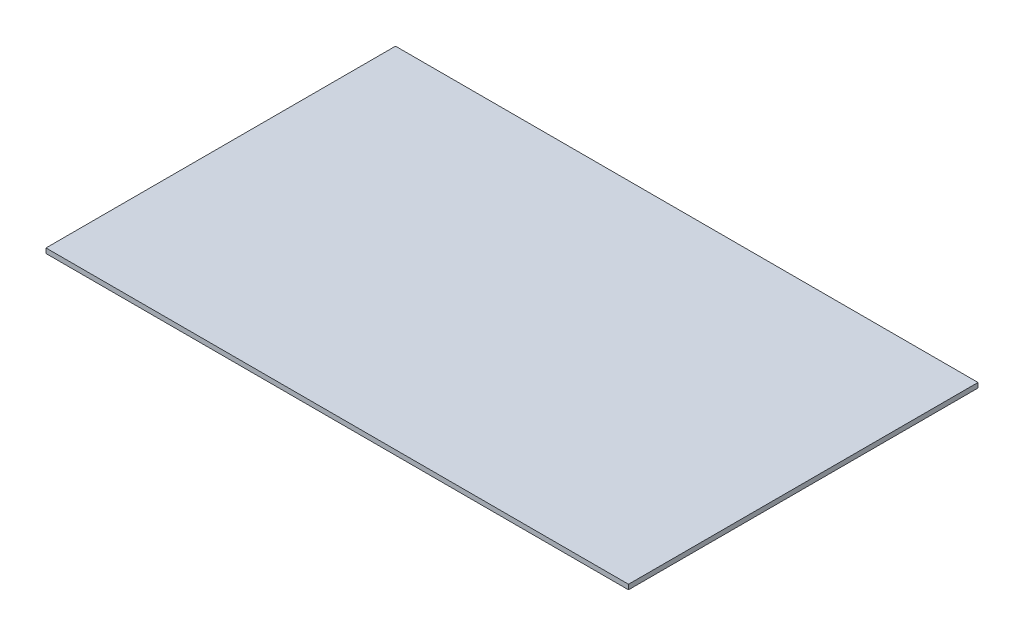
SolidWorks part; units mm, degrees
ref_plane "Front Plane" through (0, 0, 0) normal (0, 0, 1) x (1, 0, 0)
ref_plane "Top Plane" through (0, 0, 0) normal (0, 1, 0) x (1, 0, 0)
ref_plane "Right Plane" through (0, 0, 0) normal (1, 0, 0) x (0, 0, -1)
sketch "Sketch1" plane through (0, 0, 0) normal (0, 1, 0) x (1, 0, 0)
  line L1 (-1524, -914.4) -> (1524, -914.4)
  line L2 (-1524, -914.4) -> (-1524, 914.4)
  line L3 (-1524, 914.4) -> (1524, 914.4)
  line L4 (1524, -914.4) -> (1524, 914.4)
  line L5 (-1524, -914.4) -> (1524, 914.4) construction
  line L6 (-1524, 914.4) -> (1524, -914.4) construction
  point P0 (0, 0)
  dimension "D1" = 3048
  dimension "D2" = 1828.8
extrude "Boss-Extrude1" add sketch "Sketch1" along normal blind 25.4
